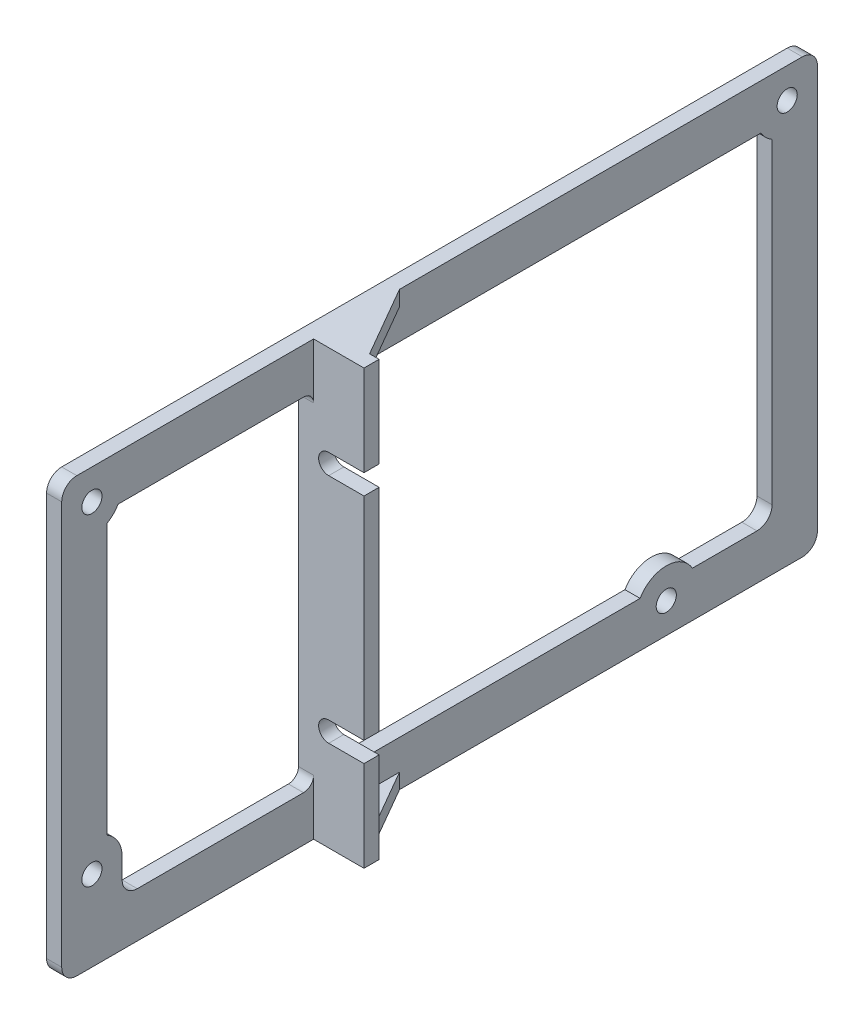
SolidWorks part; units mm, degrees
ref_plane "Спереди" through (0, 0, 0) normal (0, 0, 1) x (1, 0, 0)
ref_plane "Сверху" through (0, 0, 0) normal (0, 1, 0) x (1, 0, 0)
ref_plane "Справа" through (0, 0, 0) normal (1, 0, 0) x (0, 0, -1)
sketch "Эскиз1" plane through (0, 0, 0) normal (1, 0, 0) x (0, 0, -1)
  line L0 (0, 3) -> (0, 83)
  line L9 (150, 83) -> (150, 3)
  line L10 (147, 0) -> (3, 0)
  line L11 (3, 86) -> (147, 86)
  line L12 (9, 74.8038) -> (9, 21.1962)
  line L13 (15, 9) -> (114.8038, 9)
  line L15 (141, 12) -> (141, 74.8038)
  line L16 (138.8038, 77) -> (11.1962, 77)
  line L18 (12, 16) -> (12, 12)
  line L20 (138, 9) -> (125.1962, 9)
  circle A0 centre (6, 80) radius 2
  circle A1 centre (144, 80) radius 2
  circle A2 centre (120, 6) radius 2
  circle A3 centre (6, 16) radius 2
  arc A8 (9, 21.1962) -> (12, 16) centre (6, 16) cw
  arc A9 (11.1962, 77) -> (9, 74.8038) centre (6, 80) cw
  arc A10 (150, 83) -> (147, 86) centre (147, 83) ccw
  arc A11 (150, 3) -> (147, 0) centre (147, 3) cw
  arc A12 (3, 0) -> (0, 3) centre (3, 3) cw
  arc A13 (0, 83) -> (3, 86) centre (3, 83) cw
  arc A14 (114.8038, 9) -> (125.1962, 9) centre (120, 6) cw
  arc A15 (138.8038, 77) -> (141, 74.8038) centre (144, 80) ccw
  arc A16 (138, 9) -> (141, 12) centre (138, 12) ccw
  arc A17 (12, 12) -> (15, 9) centre (15, 12) ccw
  dimension "D1" = 4
  dimension "D2" = 4
  dimension "D3" = 4
  dimension "D4" = 4
  dimension "D16" = 6
  dimension "D17" = 6
  dimension "D18" = 3
  dimension "D19" = 3
  dimension "D20" = 3
  dimension "D21" = 3
  dimension "D22" = 6
  dimension "D23" = 6
  dimension "D26" = 3
  dimension "D27" = 3
  dimension "D5" = 6
  dimension "D6" = 16
  dimension "D7" = 64
  dimension "D8" = 138
  dimension "D9" = 114
  dimension "D10" = 74
  dimension "D11" = 6
  dimension "D12" = 9
  dimension "D13" = 9
  dimension "D14" = 9
  dimension "D15" = 9
  dimension "D24" = 150
  dimension "D25" = 86
extrude "Бобышка-Вытянуть1" add sketch "Эскиз1" along normal blind 3
ref_plane "Плоскость4" through (0, 0, -50) normal (0, 0, -1) x (-1, 0, 0)
sketch "Эскиз2" plane through (0, 0, -50) normal (0, 0, -1) x (-1, 0, 0)
  line L10 (0, 86) -> (-13, 86)
  line L12 (0, 86) -> (0, 0)
  line L13 (0, 0) -> (-13, 0)
  line L14 (-13, 86) -> (-13, 68)
  line L15 (-13, 64) -> (-6, 64)
  line L16 (-6, 22) -> (-13, 22)
  line L18 (-13, 18) -> (-6, 18)
  line L19 (-6, 68) -> (-13, 68)
  line L21 (-13, 18) -> (-13, 0)
  line L22 (-13, 64) -> (-13, 22)
  arc A0 (-6, 64) -> (-6, 68) centre (-6, 66) ccw
  arc A1 (-6, 18) -> (-6, 22) centre (-6, 20) ccw
  dimension "D2" = 4
  dimension "D3" = 4
  dimension "D1" = 20
  dimension "D5" = 20
  dimension "D4" = 7
  dimension "D6" = 13
extrude "Бобышка-Вытянуть2" add sketch "Эскиз2" along normal blind 3
sketch "Эскиз4" plane through (0, 86, 0) normal (0, 1, 0) x (1, 0, 0)
  line L0 (11.1124, 53) -> (3, 67.0511)
  line L3 (3, 53) -> (13, 53) construction
  line L4 (3, 147) -> (3, 53) construction
  dimension "D1" = 30
rib "Ребро6" sketch "Эскиз4" sketch "Эскиз4" thickness 3 extrusion direction parallel to sketch draft on no parameters "D1"=3
sketch "Эскиз5" plane through (0, 0, 0) normal (0, -1, 0) x (1, 0, 0)
  line L0 (11.1124, -53) -> (3, -67.0511)
  line L1 (3, -53) -> (3, -147) construction
  line L2 (11.1124, -53) -> (3, -67.0511) construction
rib "Ребро7" sketch "Эскиз5" sketch "Эскиз5" thickness 3 extrusion direction parallel to sketch draft on no parameters "D1"=3
fillet "Скругление1" radius 2 4 edges at (1.5, 77, -50) (1.5, 9, -50) (1.5, 77, -53) (1.5, 9, -53)
equation "\"MountHoleDiam\"= 4"
equation "\"D1@Эскиз1\"=\"MountHoleDiam\""
equation "\"D4@Эскиз1\"=\"MountHoleDiam\""
equation "\"D3@Эскиз1\"=\"MountHoleDiam\""
equation "\"D2@Эскиз1\"=\"MountHoleDiam\""
equation "\"D2@Эскиз2\"=\"MountHoleDiam\""
equation "\"D3@Эскиз2\"=\"MountHoleDiam\""
